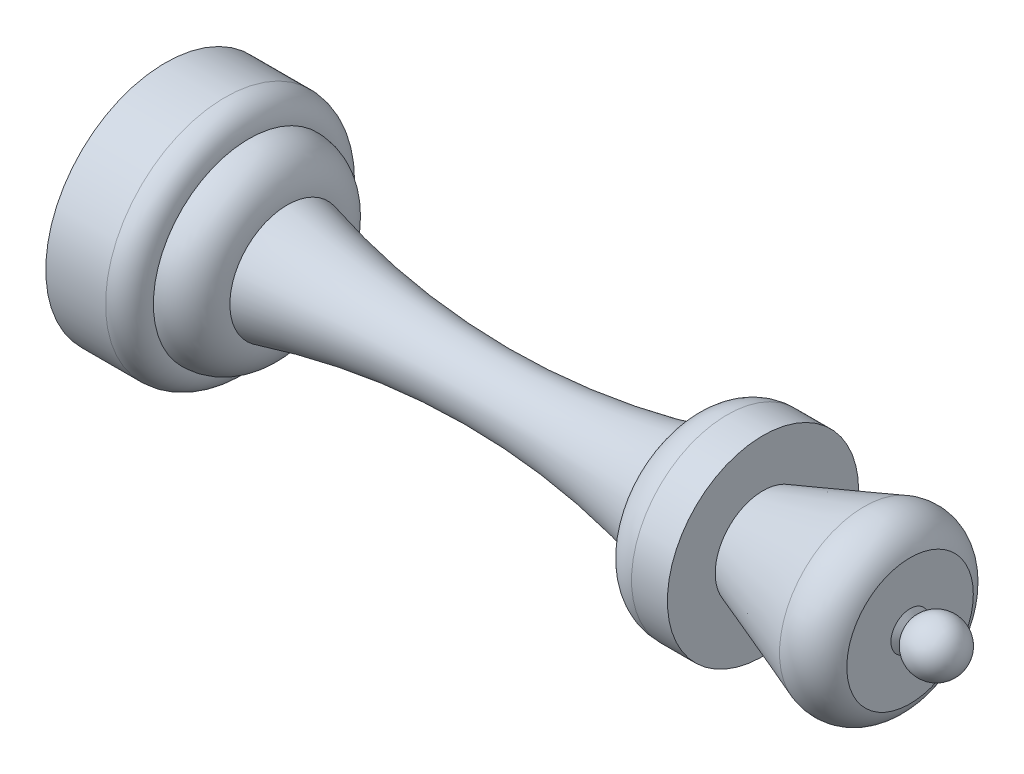
SolidWorks part; units mm, degrees
ref_plane "Спереди" through (0, 0, 0) normal (0, 0, 1) x (1, 0, 0)
ref_plane "Сверху" through (0, 0, 0) normal (0, 1, 0) x (1, 0, 0)
ref_plane "Справа" through (0, 0, 0) normal (1, 0, 0) x (0, 0, -1)
sketch "попа" plane through (0, 0, 0) normal (0, 1, 0) x (1, 0, 0)
  line L0 (0, 0) -> (0, 10)
  line L1 (0, 10) -> (5, 10)
  line L2 (5, 10) -> (5, 0)
  line L3 (-24.09, 0) -> (24.09, 0) construction
  line L4 (5, 0) -> (0, 0)
  line L5 (1, 0) -> (1, 5.25)
  line L6 (1, 5.25) -> (3.5, 5.25)
  line L7 (3.5, 5.25) -> (3.5, 0)
  line L8 (7, 0) -> (7, 8)
  line L9 (10.2, 4.8) -> (10.2, 0)
  line L10 (5, 0) -> (10.2, 0)
  arc A0 (5, 10) -> (7, 8) centre (5, 8) cw
  arc A1 (7, 8) -> (10.2, 4.8) centre (7, 4.8) cw
  dimension "D6" = 2
  dimension "D8" = 3.2
  dimension "D1" = 10
  dimension "D2" = 5
  dimension "D3" = 5.25
  dimension "D4" = 2.5
  dimension "D5" = 1
  dimension "D7" = 2
sketch "верх" plane through (0, 0, 0) normal (0, 1, 0) x (1, 0, 0)
  line L0 (10.2, 0) -> (43.8, 0)
  line L1 (43.8, 0) -> (43.8, 4.8)
  line L2 (47, 0) -> (47, 8)
  line L3 (-55, 0) -> (55, 0) construction
  line L4 (43.8, 0) -> (47, 0)
  line L5 (47, 8) -> (50, 8)
  line L6 (50, 8) -> (50, 0)
  line L7 (50, 0) -> (47, 0)
  line L8 (50, 4) -> (58.4572, 7.0782)
  line L9 (58.4572, 7.0782) -> (60.4308, 1.6559) construction
  line L10 (50, 0) -> (60.8, 0)
  line L11 (62.3, 5.2917) -> (62.3, 0)
  line L12 (62.3, 0) -> (66.7, 0)
  line L13 (10.2, 4.8) -> (10.2, 0)
  line L14 (62.3, 1.6) -> (62.5947, 1.1)
  line L15 (62.3, 0) -> (60.8, 0)
  arc A0 (10.2, 4.8) -> (43.8, 4.8) centre (27, 67.5914) ccw
  arc A1 (43.8, 4.8) -> (47, 8) centre (47, 4.8) cw
  arc A2 (58.4572, 7.0782) -> (62.3, 5.2917) centre (59.4833, 4.2591) cw
  arc A4 (62.3, 0) -> (66.7, 0) centre (64.5, 0) cw
  dimension "D3" = 65
  dimension "D4" = 3.2
  dimension "D11" = 3
  dimension "D13" = 2.2
  dimension "D1" = 33.6
  dimension "D2" = 4.8
  dimension "D5" = 3.2
  dimension "D6" = 3
  dimension "D7" = 4
  dimension "D8" = 9
  dimension "D9" = 70
  dimension "D10" = 90
  dimension "D12" = 1.5
  dimension "D14" = 10.8
  dimension "D15" = 1.6
  dimension "D16" = 1.1
revolve "Повернуть1" add sketch "попа" angle 360 about L4
revolve "Повернуть2" add sketch "верх" angle 360 about L7
